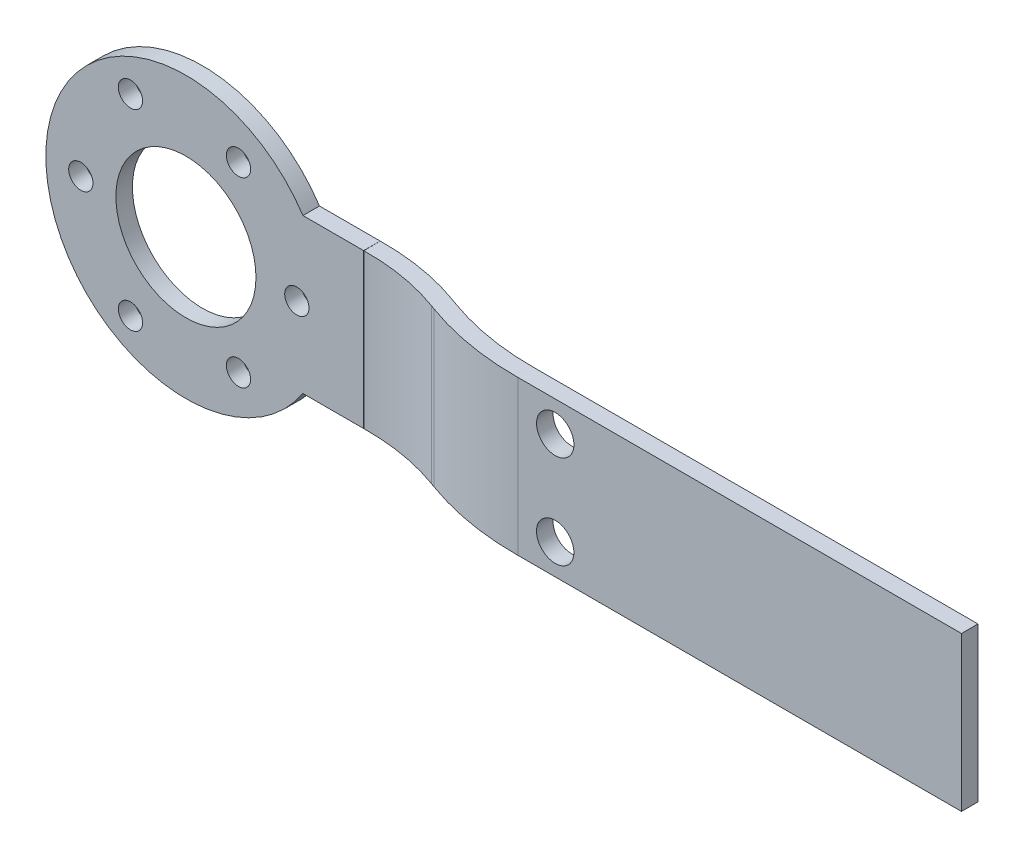
SolidWorks part; units mm, degrees
ref_plane "前视基准面" through (0, 0, 0) normal (0, 0, 1) x (1, 0, 0)
ref_plane "上视基准面" through (0, 0, 0) normal (0, 1, 0) x (1, 0, 0)
ref_plane "右视基准面" through (0, 0, 0) normal (1, 0, 0) x (0, 0, -1)
sketch "Sketch1" plane through (0, 0, 0) normal (0, 0, 1) x (1, 0, 0)
  circle A0 centre (0, 0) radius 30
extrude "Boss-Extrude1" add sketch "Sketch1" along normal blind 3.54
sketch "Sketch3" plane through (0, 0, 3.54) normal (0, 0, 1) x (1, 0, 0)
  circle A1 centre (12, 5) radius 4
  dimension "D1" = 5
  dimension "D2" = 12
sketch "Sketch4" plane through (0, 0, 3.54) normal (0, 0, 1) x (1, 0, 0)
  line L0 (25.7688, 0) -> (75.3766, 0) construction
  line L1 (25.0549, 16.5) -> (38.0549, 16.5)
  line L2 (25.0549, -16.5) -> (38.0549, -16.5)
  line L3 (30, 0) -> (30, 16.5) construction
  line L4 (38.0549, 16.5) -> (38.0549, -16.5)
  circle A0 centre (0, 0) radius 30 construction
  arc A1 (25.0549, 16.5) -> (25.0549, -16.5) centre (0, 0) cw
  dimension "D1" = 16.5
  dimension "D2" = 13
extrude "Boss-Extrude4" add sketch "Sketch4" against normal blind 3.54
sketch "Sketch5" plane through (0, 0, 3.54) normal (0, 0, 1) x (1, 0, 0)
  circle A0 centre (0, 0) radius 15
  dimension "D1" = 30
extrude "Cut-Extrude1" cut sketch "Sketch5" against normal up to next
sketch "Sketch6" plane through (0, 0, 3.54) normal (0, 0, 1) x (1, 0, 0)
  circle A0 centre (0, 0) radius 22.5 construction
  circle A1 centre (-22.5, 0) radius 2.6
  circle A2 centre (11.25, 19.4856) radius 2.6
  circle A3 centre (11.25, -19.4856) radius 2.6
  circle A4 centre (0, 0) radius 23.75 construction
  circle A5 centre (23.75, 0) radius 2.6
  circle A6 centre (-11.875, -20.5681) radius 2.6
  circle A7 centre (-11.875, 20.5681) radius 2.6
  dimension "D1" = 45
  dimension "D2" = 3
  dimension "D3" = 47.5
  dimension "D4" = 3
extrude "Cut-Extrude2" cut sketch "Sketch6" against normal up to next
sketch "Sketch7" plane through (0, 16.5, 0) normal (0, 1, 0) x (1, 0, 0)
  line L0 (78.0549, -7) -> (173.0549, -7)
  line L1 (38.0549, 0) -> (25.0549, 0) construction
  line L2 (38.0549, 0) -> (38.0549, -3.54) construction
  line L3 (55.497, -6.4884) -> (56.408, -6.82)
  line L4 (56.7077, -3.1619) -> (57.6187, -3.4934)
  line L5 (78.071, -10.54) -> (173.0549, -10.54)
  line L6 (38.0549, 0) -> (38.1018, -3.5397)
  line L7 (173.0549, -7) -> (173.0549, -10.54)
  arc A0 (38.0549, 0) -> (56.7077, -3.1619) centre (38.7498, -52.5007) cw
  arc A1 (78.0549, -7) -> (57.6187, -3.4934) centre (77.5194, 51.1832) cw
  arc A2 (38.1018, -3.5397) -> (55.497, -6.4884) centre (38.7498, -52.5007) cw
  arc A3 (78.071, -10.54) -> (56.408, -6.82) centre (77.5194, 51.1832) cw
  dimension "D1" = 7
  dimension "D2" = 40
  dimension "D3" = 3.54
  dimension "D4" = 95
extrude "Boss-Extrude5" add sketch "Sketch7" against normal up to surface (33 mm away) separate body up to face at (31.5549, -16.5, 1.77)
sketch "Sketch8" plane through (0, 0, 10.54) normal (0, 0, 1) x (1, 0, 0)
  line L0 (86.071, 15.4413) -> (86.071, -8.4863) construction
  line L1 (93.673, 0) -> (79.5285, 0) construction
  line L2 (78.071, -16.5) -> (78.071, 16.5) construction
  circle A0 centre (86.071, 10) radius 4
  circle A1 centre (86.071, -10) radius 4
  dimension "D1" = 10
  dimension "D2" = 8
extrude "Cut-Extrude3" cut sketch "Sketch8" against normal blind 10
